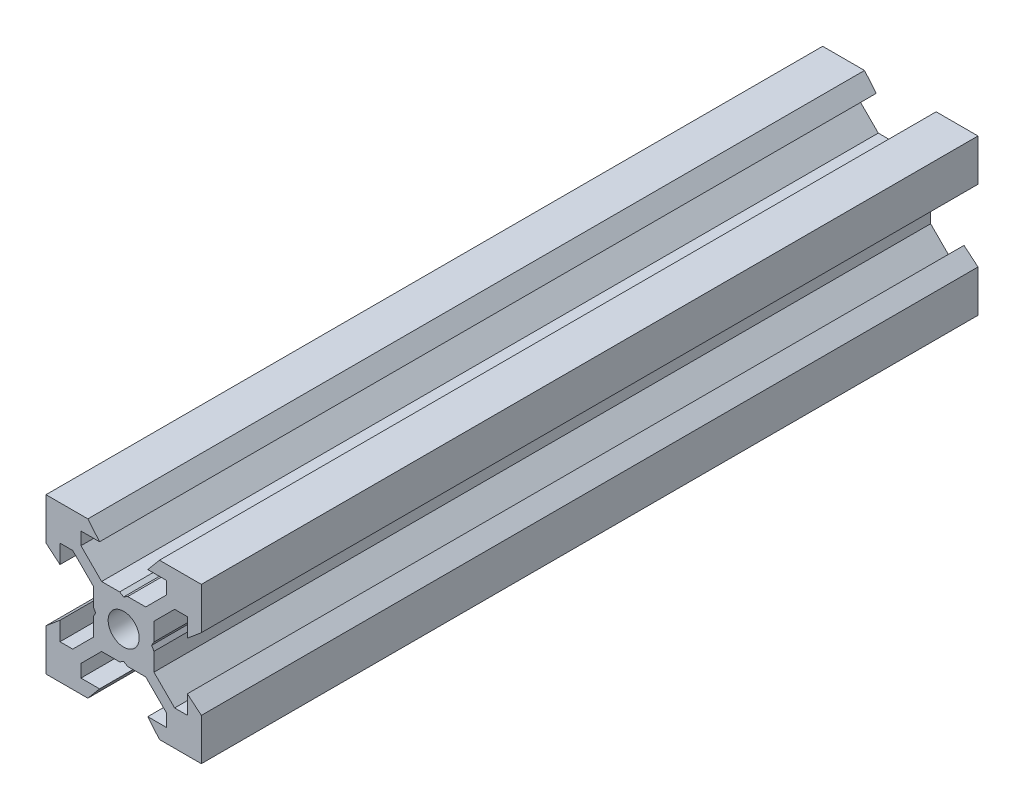
SolidWorks part; units mm, degrees
ref_plane "Front Plane" through (0, 0, 0) normal (0, 0, 1) x (1, 0, 0)
ref_plane "Top Plane" through (0, 0, 0) normal (0, 1, 0) x (1, 0, 0)
ref_plane "Right Plane" through (0, 0, 0) normal (1, 0, 0) x (0, 0, -1)
sketch "Sketch1" plane through (0, 0, 0) normal (0, 0, 1) x (1, 0, 0)
  line L0 (10, 10) -> (4.6104, 10) construction
  line L1 (10, 10) -> (10, 4.6104) construction
  line L2 (10, -10) -> (10, -4.6104) construction
  line L3 (10, -10) -> (4.6104, -10) construction
  line L4 (10, 10) -> (10, 4.6104)
  line L5 (6.5607, 5.5) -> (8.2, 5.5)
  line L6 (5.5, 8.2) -> (5.5, 6.5607)
  line L7 (10, 10) -> (4.6104, 10)
  line L8 (10, 10) -> (10, 4.6104)
  line L9 (6.5607, 5.5) -> (3.9, 2.8393)
  line L10 (5.5, 6.5607) -> (2.8393, 3.9)
  line L11 (10, 4.6104) -> (8.2, 3.1)
  line L12 (4.6104, 10) -> (3.1, 8.2)
  line L13 (8.2, 3.1) -> (8.2, 5.5)
  line L14 (3.1, 8.2) -> (5.5, 8.2)
  line L15 (-6.5607, 5.5) -> (-8.2, 5.5)
  line L16 (6.5607, -5.5) -> (8.2, -5.5)
  line L17 (3.1, -8.2) -> (5.5, -8.2)
  line L18 (8.2, -3.1) -> (8.2, -5.5)
  line L19 (4.6104, -10) -> (3.1, -8.2)
  line L20 (10, -4.6104) -> (8.2, -3.1)
  line L21 (0.5196, -3.9) -> (0, -3.6)
  line L22 (0.5196, 3.9) -> (0, 3.6)
  line L23 (3.6, 0) -> (3.9, -0.5196)
  line L24 (3.9, 0.5196) -> (3.6, 0)
  line L25 (3.9, 0.5196) -> (3.9, 2.8393)
  line L26 (2.8393, 3.9) -> (0.5196, 3.9)
  line L27 (3.9, -2.8393) -> (3.9, -0.5196)
  line L28 (2.8393, -3.9) -> (0.5196, -3.9)
  line L29 (5.5, -6.5607) -> (2.8393, -3.9)
  line L30 (6.5607, -5.5) -> (3.9, -2.8393)
  line L31 (10, -10) -> (10, -4.6104)
  line L32 (10, -10) -> (4.6104, -10)
  line L33 (5.5, -8.2) -> (5.5, -6.5607)
  line L34 (-6.5607, -5.5) -> (-8.2, -5.5)
  line L35 (10, -10) -> (10, -4.6104)
  line L36 (0, 0) -> (0, 8.2) construction
  line L37 (-10, -10) -> (-4.6104, -10) construction
  line L38 (-10, -10) -> (-10, -4.6104) construction
  line L39 (-10, 10) -> (-10, 4.6104) construction
  line L40 (-10, 10) -> (-4.6104, 10) construction
  line L41 (-10, -10) -> (-10, -4.6104)
  line L43 (-5.5, -8.2) -> (-5.5, -6.5607)
  line L44 (-10, -10) -> (-4.6104, -10)
  line L45 (-10, -10) -> (-10, -4.6104)
  line L46 (-6.5607, -5.5) -> (-3.9, -2.8393)
  line L47 (-5.5, -6.5607) -> (-2.8393, -3.9)
  line L48 (-2.8393, -3.9) -> (-0.5196, -3.9)
  line L49 (-3.9, -2.8393) -> (-3.9, -0.5196)
  line L50 (-2.8393, 3.9) -> (-0.5196, 3.9)
  line L51 (-3.9, 0.5196) -> (-3.9, 2.8393)
  line L52 (-3.9, 0.5196) -> (-3.6, 0)
  line L53 (-3.6, 0) -> (-3.9, -0.5196)
  line L54 (-0.5196, 3.9) -> (0, 3.6)
  line L55 (-0.5196, -3.9) -> (0, -3.6)
  line L56 (-10, -4.6104) -> (-8.2, -3.1)
  line L57 (-4.6104, -10) -> (-3.1, -8.2)
  line L58 (-8.2, -3.1) -> (-8.2, -5.5)
  line L59 (-3.1, -8.2) -> (-5.5, -8.2)
  line L60 (-10, -10) -> (10, -10) construction
  line L61 (-10, -10) -> (-10, 10) construction
  line L62 (-3.1, 8.2) -> (-5.5, 8.2)
  line L63 (-8.2, 3.1) -> (-8.2, 5.5)
  line L64 (-4.6104, 10) -> (-3.1, 8.2)
  line L65 (-10, 4.6104) -> (-8.2, 3.1)
  line L66 (-5.5, 6.5607) -> (-2.8393, 3.9)
  line L67 (-6.5607, 5.5) -> (-3.9, 2.8393)
  line L68 (-10, 10) -> (-10, 4.6104)
  line L69 (-10, 10) -> (-4.6104, 10)
  line L70 (-5.5, 8.2) -> (-5.5, 6.5607)
  line L71 (-10, 10) -> (10, 10) construction
  line L72 (-10, 10) -> (-10, 4.6104)
  line L73 (10, -10) -> (10, 10) construction
  line L74 (-10, -10) -> (10, 10) construction
  line L75 (-10, 10) -> (10, -10) construction
  circle A0 centre (0, 0) radius 2
  dimension "D7" = 4
  dimension "D1" = 20
  dimension "D2" = 5.3896
  dimension "D3" = 4.5
  dimension "D4" = 50
  dimension "D5" = 1.8
  dimension "D6" = 1.5104
  dimension "D8" = 5.5
  dimension "D9" = 120
  dimension "D10" = 0.3
  dimension "D11" = 2.3197
  dimension "D12" = 7.8
  dimension "D13" = 7.8
  dimension "D14" = 1.5
  dimension "D15" = 2.6607
extrude "Boss-Extrude1" add sketch "Sketch1" along normal mid plane 100 contours L70 L62 L64 L69 L68 L65 L63 L15 L67 L51 L52 L53 L49 L46 L34 L58 L56 L41 L44 L57 L59 L43 L47 L48 L55 L21 L28 L29 L33 L17 L19 L32 L31 L20 L18 L16 L30 L27 L23 L24 L25 L9 L5 L13 L11 L4 L7 L12 L14 L6 L10
